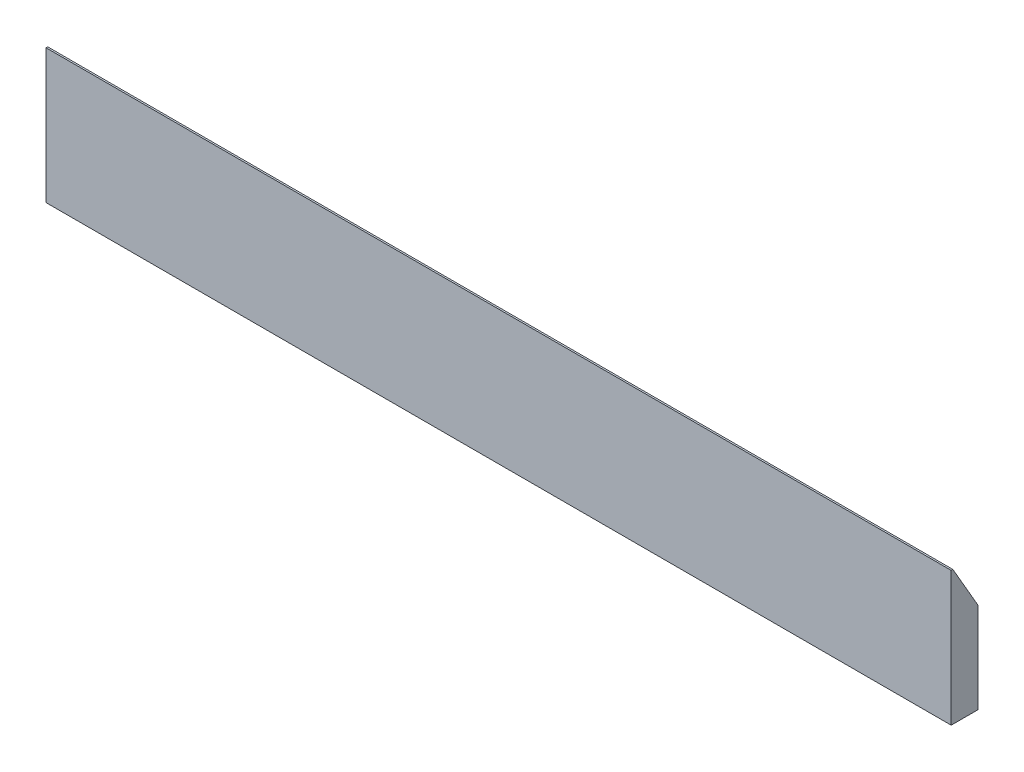
SolidWorks part; units mm, degrees
ref_plane "前视基准面" through (0, 0, 0) normal (0, 0, 1) x (1, 0, 0)
ref_plane "上视基准面" through (0, 0, 0) normal (0, 1, 0) x (1, 0, 0)
ref_plane "右视基准面" through (0, 0, 0) normal (1, 0, 0) x (0, 0, -1)
sketch "草图1" plane through (0, 0, 0) normal (0, 0, 1) x (1, 0, 0)
  line L1 (-27, -4) -> (27, -4)
  line L2 (-27, -4) -> (-27, 4)
  line L3 (-27, 4) -> (27, 4)
  line L4 (27, -4) -> (27, 4)
  line L5 (-27, -4) -> (27, 4) construction
  line L6 (-27, 4) -> (27, -4) construction
  point P0 (0, 0)
  dimension "D1" = 54
  dimension "D2" = 8
extrude "凸台-拉伸1" add sketch "草图1" along normal blind 0.4
sketch "草图2" plane through (0, 0, 0) normal (0, 0, -1) x (-1, 0, 0)
  line L0 (-27, 4) -> (27, 4) construction
  line L1 (-27, -4) -> (-24, -4)
  line L2 (-27, -4) -> (-27, 4)
  line L3 (-27, 4) -> (-24, 4)
  line L4 (-24, -4) -> (-24, 4)
  dimension "D1" = 3
extrude "凸台-拉伸2" add sketch "草图2" along normal blind 1.2
sketch "草图3" plane through (0, -4, 0) normal (0, -1, 0) x (1, 0, 0)
  line L1 (-27, 0.4) -> (27, 0.4)
  line L2 (-27, 0.4) -> (-27, -1.2)
  line L3 (-27, -1.2) -> (27, -1.2)
  line L4 (27, 0.4) -> (27, -1.2)
extrude "凸台-拉伸3" add sketch "草图3" against normal blind 2
chamfer "倒角1" distance 1.5 angle 60 1 edges at (25.5, 4, -1.2)
